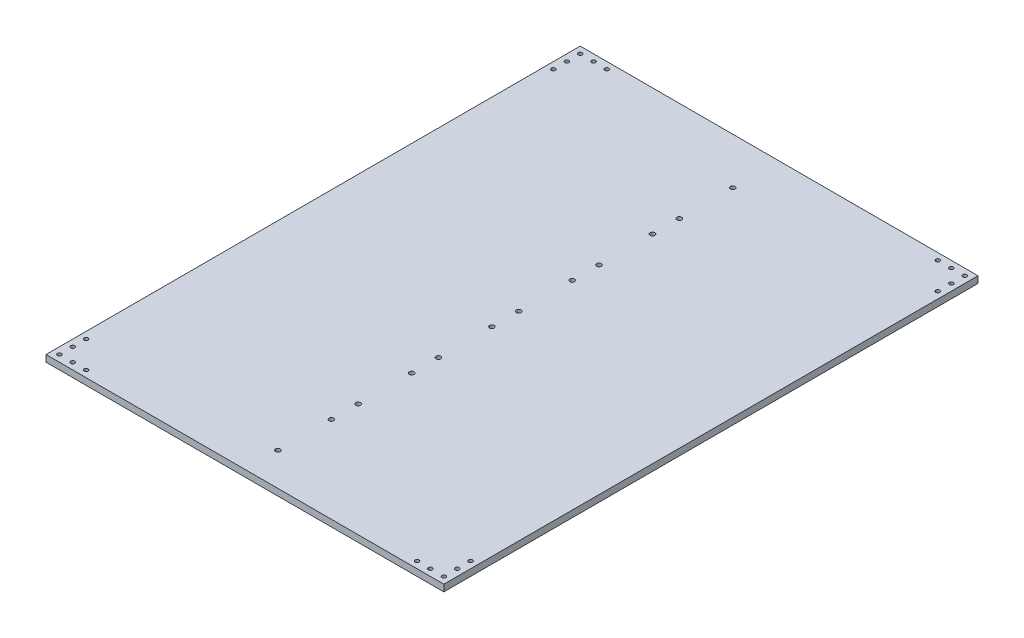
SolidWorks part; units mm, degrees
ref_plane "Front Plane" through (0, 0, 0) normal (0, 0, 1) x (1, 0, 0)
ref_plane "Top Plane" through (0, 0, 0) normal (0, 1, 0) x (1, 0, 0)
ref_plane "Right Plane" through (0, 0, 0) normal (1, 0, 0) x (0, 0, -1)
sketch "Sketch1" plane through (0, 0, 0) normal (0, 1, 0) x (1, 0, 0)
  line L1 (0, 0) -> (297.5, 0)
  line L2 (0, 0) -> (0, 399.5)
  line L3 (0, 399.5) -> (297.5, 399.5)
  line L4 (297.5, 0) -> (297.5, 399.5)
  dimension "D1" = 399.5
  dimension "D2" = 297.5
extrude "Boss-Extrude1" add sketch "Sketch1" along normal blind 5
sketch "Sketch3" plane through (0, 5, 0) normal (0, 1, 0) x (1, 0, 0)
  circle A0 centre (148.7481, 24.6847) radius 1.7499
  circle A1 centre (148.7483, 64.6837) radius 1.7504
  circle A2 centre (148.7504, 84.7207) radius 1.7502
  circle A3 centre (148.748, 124.721) radius 1.7496
  circle A4 centre (148.749, 144.7501) radius 1.751
  circle A5 centre (148.7475, 184.7526) radius 1.7486
  circle A6 centre (148.747, 204.7868) radius 1.7489
  circle A7 centre (148.7482, 244.7868) radius 1.7499
  circle A8 centre (148.747, 264.8168) radius 1.7489
  circle A9 centre (148.7502, 304.8159) radius 1.751
  circle A10 centre (148.747, 324.8528) radius 1.7489
  circle A11 centre (148.751, 364.8529) radius 1.7522
extrude "Cut-Extrude2" cut sketch "Sketch3" against normal blind 10
sketch "Sketch5" plane through (0, 5, 0) normal (0, 1, 0) x (1, 0, 0)
  line L0 (0, 0) -> (297.5, 0) construction
  line L1 (10, 10) -> (287.5, 10)
  line L2 (10, 10) -> (10, 389.5)
  line L3 (10, 389.5) -> (287.5, 389.5)
  line L4 (287.5, 10) -> (287.5, 389.5)
  line L5 (0, 399.5) -> (0, 0) construction
  line L6 (297.5, 399.5) -> (0, 399.5) construction
  line L7 (297.5, 0) -> (297.5, 399.5) construction
  line L8 (0, 199.75) -> (297.5, 199.75)
  line L9 (148.75, 0) -> (148.75, 399.5)
  circle A0 centre (5, 5) radius 1.5
  circle A1 centre (5, 15) radius 1.5
  circle A2 centre (15, 5) radius 1.5
  circle A3 centre (5, 25) radius 1.5
  circle A4 centre (25, 5) radius 1.5
  circle A5 centre (25, 394.5) radius 1.5
  circle A6 centre (15, 394.5) radius 1.5
  circle A7 centre (5, 374.5) radius 1.5
  circle A8 centre (5, 384.5) radius 1.5
  circle A9 centre (5, 394.5) radius 1.5
  circle A10 centre (292.5, 374.5) radius 1.5
  circle A11 centre (292.5, 384.5) radius 1.5
  circle A12 centre (292.5, 394.5) radius 1.5
  circle A13 centre (282.5, 394.5) radius 1.5
  circle A14 centre (272.5, 394.5) radius 1.5
  circle A15 centre (292.5, 25) radius 1.5
  circle A16 centre (292.5, 15) radius 1.5
  circle A17 centre (292.5, 5) radius 1.5
  circle A18 centre (282.5, 5) radius 1.5
  circle A19 centre (272.5, 5) radius 1.5
  dimension "D5" = 3
  dimension "D6" = 5
  dimension "D7" = 5
  dimension "D8" = 3
  dimension "D9" = 3
  dimension "D10" = 3
  dimension "D11" = 3
  dimension "D12" = 5
  dimension "D13" = 5
  dimension "D14" = 5
  dimension "D15" = 5
  dimension "D16" = 10
  dimension "D17" = 10
  dimension "D18" = 10
  dimension "D19" = 10
  dimension "D1" = 10
  dimension "D2" = 10
  dimension "D3" = 10
  dimension "D4" = 10
extrude "Cut-Extrude3" cut sketch "Sketch5" against normal blind 10 contours A19 | A18 | A17 | A16 | A15 | A10 | A11 | A12 | A13 | A14 | A7 | A8 | A9 | A6 | A5 | A4 | A2 | A0 | A1 | A3
